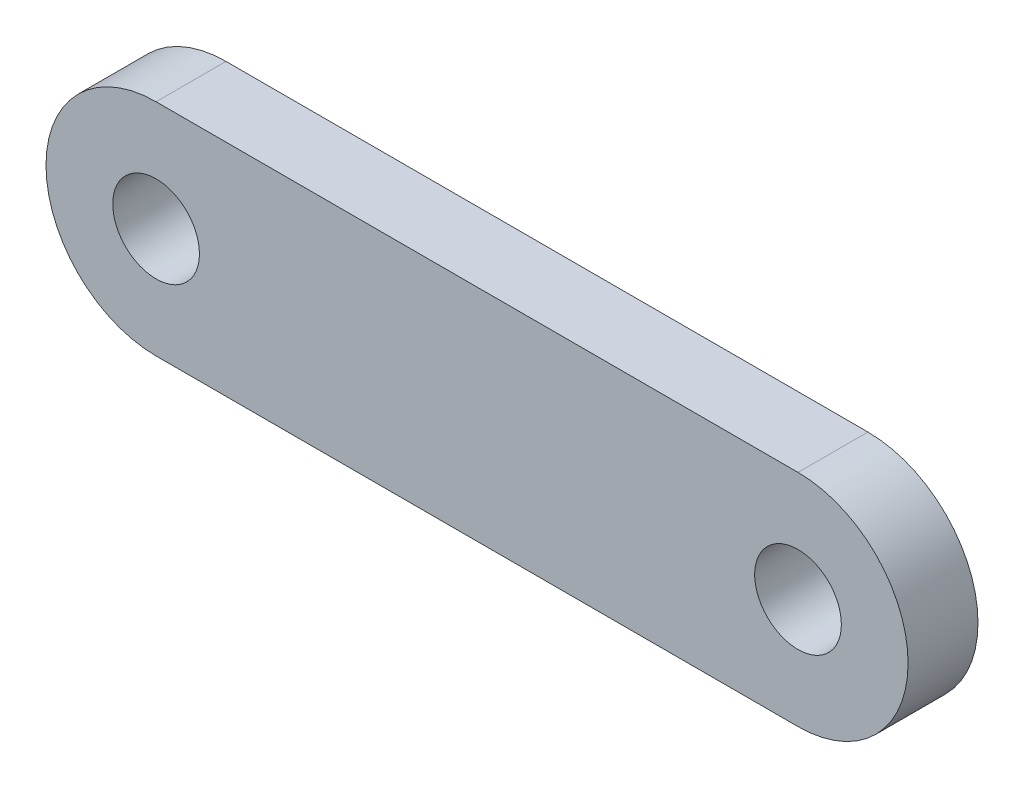
SolidWorks part; units mm, degrees
material "Balsa"
ref_plane "Front Plane" through (0, 0, 0) normal (0, 0, 1) x (1, 0, 0)
ref_plane "Top Plane" through (0, 0, 0) normal (0, 1, 0) x (1, 0, 0)
ref_plane "Right Plane" through (0, 0, 0) normal (1, 0, 0) x (0, 0, -1)
sketch "Sketch1" plane through (0, 0, 0) normal (0, 0, 1) x (1, 0, 0)
  line L0 (-29.1547, 0) -> (29.1547, 0) construction
  line L1 (-29.1547, 10) -> (29.1547, 10)
  line L2 (-29.1547, -10) -> (29.1547, -10)
  arc A0 (-29.1547, 10) -> (-29.1547, -10) centre (-29.1547, 0) ccw
  arc A1 (29.1547, -10) -> (29.1547, 10) centre (29.1547, 0) ccw
  circle A2 centre (-29.1547, 0) radius 3.9375
  circle A3 centre (29.1547, 0) radius 3.9375
  point P2 (0, 0)
  dimension "D3" = 7.875
  dimension "D4" = 7.875
  dimension "D1" = 20
  dimension "D2" = 58.3093
extrude "Boss-Extrude1" add sketch "Sketch1" along normal blind 6.35
